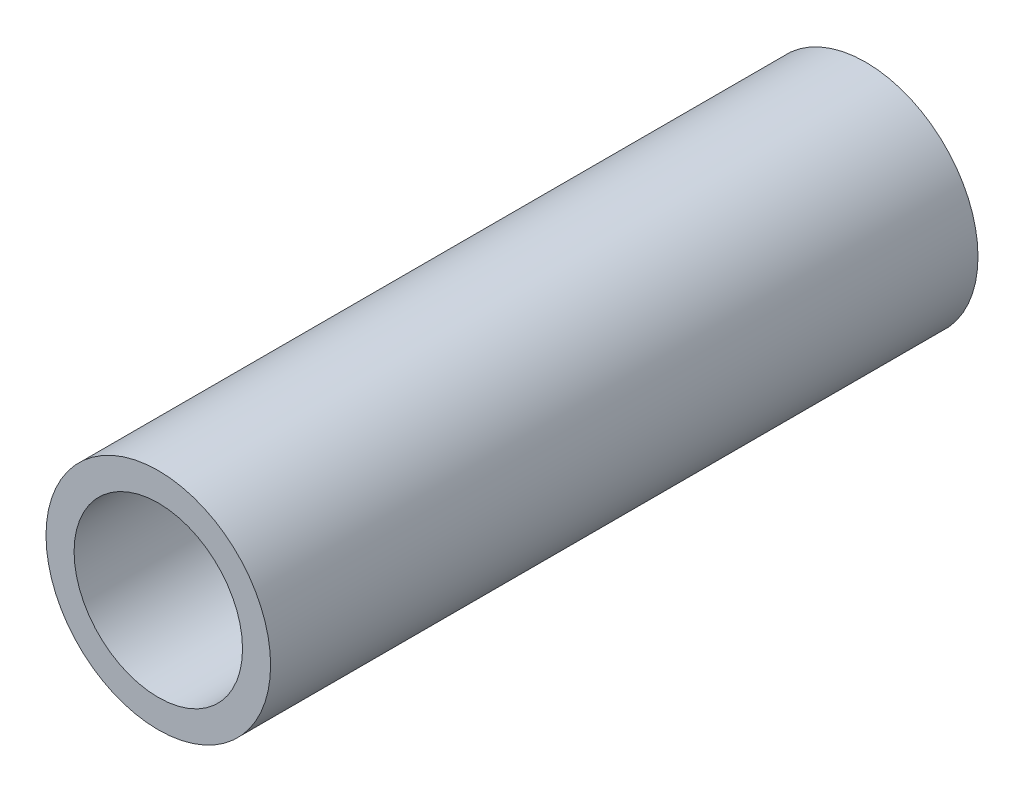
SolidWorks part; units mm, degrees
material "Cobre"
ref_plane "Plano frontal" through (0, 0, 0) normal (0, 0, 1) x (1, 0, 0)
ref_plane "Plano superior" through (0, 0, 0) normal (0, 1, 0) x (1, 0, 0)
ref_plane "Plano direito" through (0, 0, 0) normal (1, 0, 0) x (0, 0, -1)
sketch "Esboço1" plane through (0, 0, 0) normal (0, 0, 1) x (1, 0, 0)
  circle A0 centre (0, 0) radius 3.175
  circle A1 centre (0, 0) radius 2.3813
  dimension "D1" = 6.35
  dimension "D2" = 4.7625
extrude "Ressalto-extrusão1" add sketch "Esboço1" along normal blind 20
